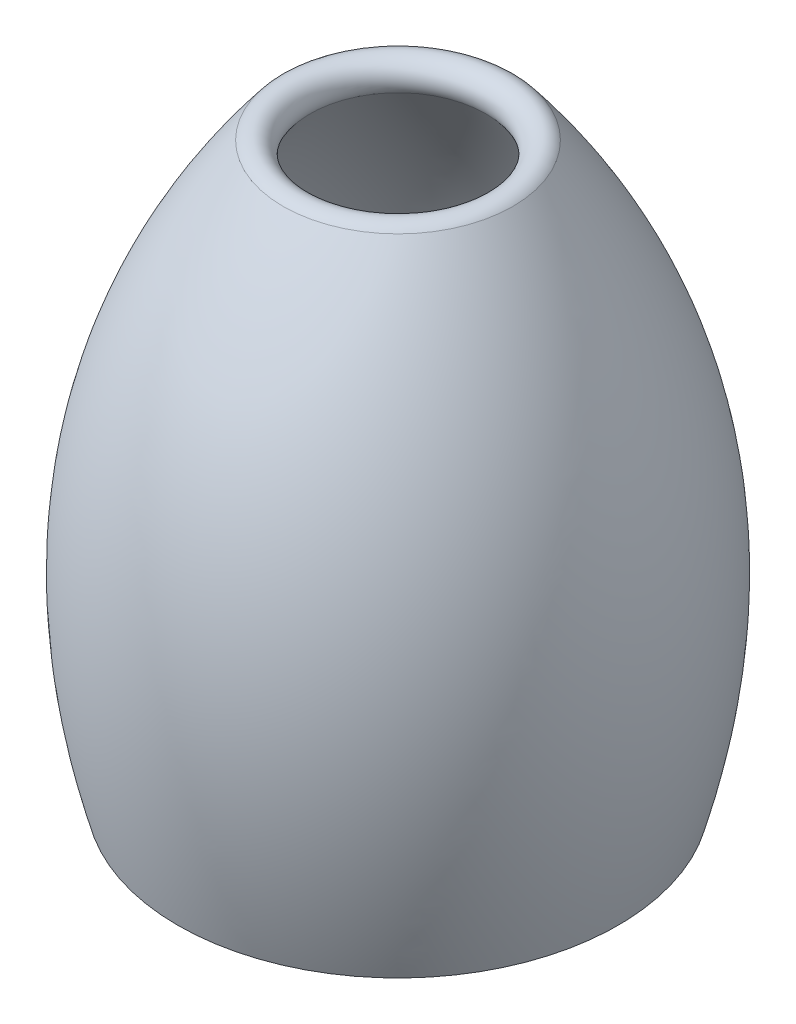
SolidWorks part; units mm, degrees
ref_plane "Front Plane" through (0, 0, 0) normal (0, 0, 1) x (1, 0, 0)
ref_plane "Top Plane" through (0, 0, 0) normal (0, 1, 0) x (1, 0, 0)
ref_plane "Right Plane" through (0, 0, 0) normal (1, 0, 0) x (0, 0, -1)
sketch "Sketch2" plane through (0, 0, 0) normal (0, 0, 1) x (1, 0, 0)
  line L0 (0, 0) -> (4.8141, 1.3506)
  line L1 (32.1833, 1.3506) -> (32.1833, 56.8614) construction
  arc A0 (15.392, 83.3204) -> (19.3226, 80.23) centre (17.1729, 81.5407) cw
  spline S0 degree 2 poles (0, 0) (-13.1801, 46.98) (15.392, 83.3204) knots 0 0 0 1 1 1
  spline S1 degree 1 poles (4.8141, 1.3506) (19.3226, 80.23) knots 0 0 1 1 construction
  spline S2 degree 2 poles (4.8141, 1.3506) (0.0928, 18.2626) (1.5648, 43.5761) (9.1368, 67.2467) (19.3226, 80.23) knots 0 0 0 0.375 0.625 1 1 1
  point P9 (32.1833, 56.8614)
  dimension "D1" = 5
revolve "Revolve5" add sketch "Sketch2" angle 360 about L1
